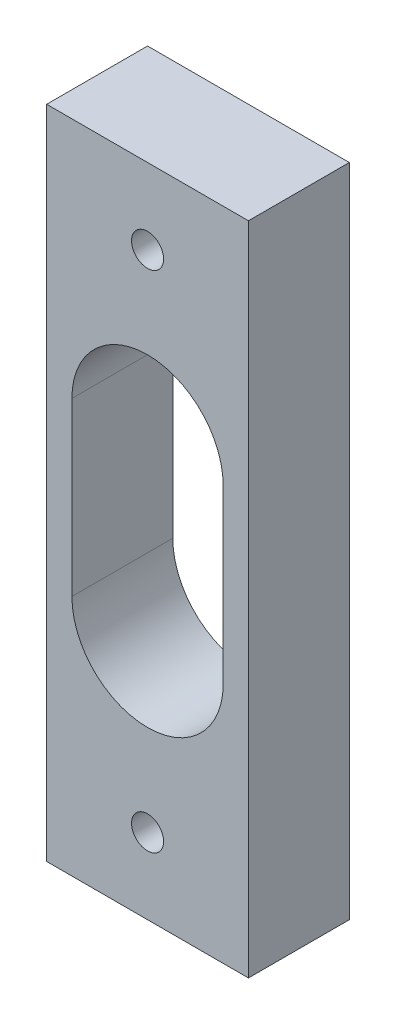
SolidWorks part; units mm, degrees
material "6061-T6 AL"
ref_plane "Front" through (0, 0, 0) normal (0, 0, 1) x (1, 0, 0)
ref_plane "Top" through (0, 0, 0) normal (0, 1, 0) x (1, 0, 0)
ref_plane "Right" through (0, 0, 0) normal (1, 0, 0) x (0, 0, -1)
sketch "Sketch1" plane through (0, 0, 0) normal (0, 1, 0) x (1, 0, 0)
  line L0 (0, 0) -> (0, 12.7)
  line L1 (0, 0) -> (25.4, 0)
  line L2 (0, 12.7) -> (25.4, 12.7)
  line L3 (25.4, 0) -> (25.4, 12.7)
  dimension "D1" = 12.7
  dimension "D2" = 25.4
extrude "Boss-Extrude1" add sketch "Sketch1" along normal blind 82.55
hole_wizard "#10-32 Tapped Hole - Top Hold" positions "Sketch4" profile "Sketch5" tap size "#10-32" standard "ANSI Inch" end condition through all
sketch "Sketch4" plane through (0, 0, -12.7) normal (0, 0, -1) x (-1, 0, 0)
  line L0 (0, 41.275) -> (-25.4, 41.275) construction
  line L4 (0, 82.55) -> (0, 0) construction
  line L8 (-25.4, 82.55) -> (-25.4, 0) construction
  line L9 (-12.7, 41.275) -> (-12.7, 73.025) construction
  line L11 (-12.7, 41.275) -> (-12.7, 9.525) construction
  point P22 (-12.7, 73.025)
  point P27 (-12.7, 9.525)
  dimension "D1" = 31.75
cosmetic thread "Hole Thread3"
cosmetic thread "Hole Thread4"
sketch "Sketch5" plane through (12.7, 9.525, -12.7) normal (1, 0, 0) x (0, 1, 0)
  line L0 (0, 0) -> (0, 12.7)
  line L1 (0, 12.7) -> (2.0193, 12.7)
  line L2 (2.0193, 12.7) -> (2.0193, 0)
  line L5 (2.0193, 0) -> (0, 0)
  line L11 (0, -6.35) -> (0, 107.95) construction
  dimension "Thru Tap Drill Dia." = 4.0386
  dimension "Thru Tap Drill Depth" = 12.7
hole_wizard "#8-32 Tapped Hole - Side Plate" positions "Sketch6" profile "Sketch7" tap size "#8-32" standard "ANSI Inch"
sketch "Sketch6" plane through (0, 0, 0) normal (-1, 0, 0) x (0, 0, 1)
  line L0 (-12.7, 41.275) -> (0, 41.275) construction
  line L1 (-12.7, 82.55) -> (-12.7, 0) construction
  line L2 (0, 82.55) -> (0, 0) construction
  line L4 (-6.35, 19.05) -> (-6.35, 63.5) construction
  point P0 (-6.35, 19.05)
  point P2 (-6.35, 63.5)
  point P15 (-6.35, 41.275)
  point P16 (-6.35, 41.275)
  dimension "D1" = 22.225
cosmetic thread "Hole Thread5"
cosmetic thread "Hole Thread6"
sketch "Sketch7" plane through (0, 19.05, -6.35) normal (0, 1, 0) x (0, 0, 1)
  line L0 (0, 0) -> (0, 13.3314)
  line L1 (0, 13.3314) -> (1.7272, 12.2936)
  line L2 (1.7272, 12.2936) -> (1.7272, 0)
  line L5 (1.7272, 0) -> (0, 0)
  line L10 (0, 13.3314) -> (-1.7272, 12.2936) construction
  line L11 (0, -6.35) -> (0, 107.95) construction
  dimension "Tap Drill Dia." = 3.4544
  dimension "Tap Drill Depth" = 12.2936
  dimension "Drill Angle" = 118
sketch "Sketch8" plane through (0, 0, -12.7) normal (0, 0, -1) x (-1, 0, 0)
  line L0 (-12.7, 30.48) -> (-12.7, 52.07) construction
  line L1 (-22.225, 30.48) -> (-22.225, 52.07)
  line L2 (-3.175, 30.48) -> (-3.175, 52.07)
  line L3 (-12.7, 41.275) -> (-25.4, 41.275) construction
  line L4 (-25.4, 82.55) -> (-25.4, 0) construction
  arc A0 (-22.225, 30.48) -> (-3.175, 30.48) centre (-12.7, 30.48) ccw
  arc A1 (-3.175, 52.07) -> (-22.225, 52.07) centre (-12.7, 52.07) ccw
  point P3 (-12.7, 41.275)
  dimension "D2" = 9.525
  dimension "D1" = 21.59
extrude "Cut-Extrude1" cut sketch "Sketch8" against normal through all
